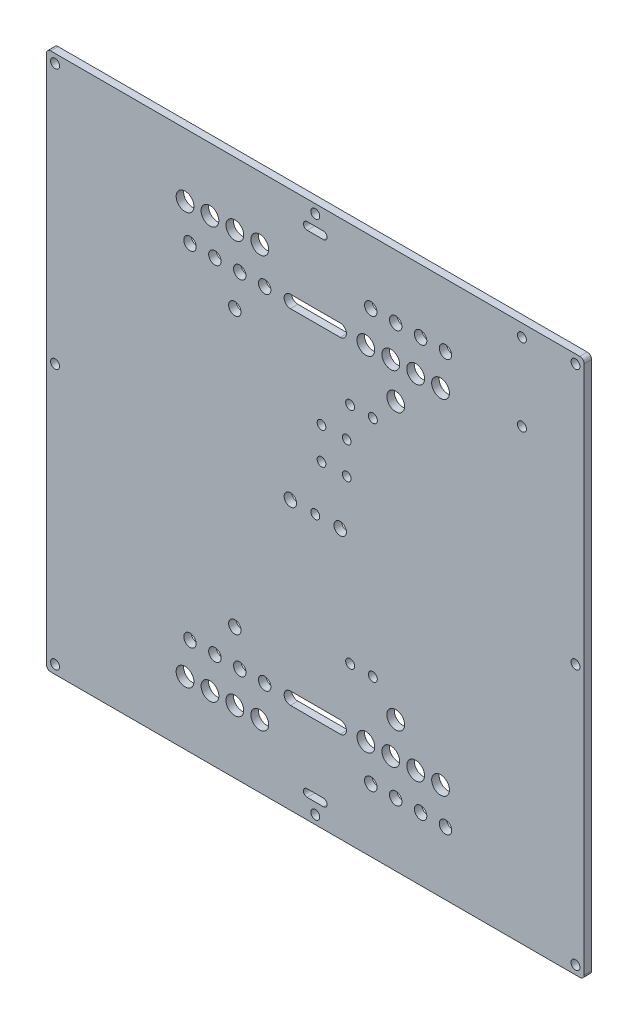
SolidWorks part; units mm, degrees
ref_plane "Plan de face" through (0, 0, 0) normal (0, 0, 1) x (1, 0, 0)
ref_plane "Plan de dessus" through (0, 0, 0) normal (0, 1, 0) x (1, 0, 0)
ref_plane "Plan de droite" through (0, 0, 0) normal (1, 0, 0) x (0, 0, -1)
sketch "Esquisse1" plane through (0, 0, 0) normal (0, 0, 1) x (1, 0, 0)
  line L0 (-3.25, -98.62) -> (3.25, -98.62) construction
  line L1 (-106.25, -108) -> (106.25, -108)
  line L2 (-108, -106.25) -> (-108, 106.25)
  line L3 (-106.25, 108) -> (106.25, 108)
  line L4 (108, -106.25) -> (108, 106.25)
  line L5 (-108, -108) -> (108, 108) construction
  line L6 (-108, 108) -> (108, -108) construction
  line L7 (-3.25, -97.12) -> (3.25, -97.12)
  line L8 (-3.25, -100.12) -> (3.25, -100.12)
  line L9 (0, -98.62) -> (0, -104.5) construction
  line L10 (-10, -69) -> (10, -69) construction
  line L11 (-10, -66.5) -> (10, -66.5)
  line L12 (-10, -71.5) -> (10, -71.5)
  line L13 (0, -69) -> (0, -98.62) construction
  line L14 (-32.3, -55.35) -> (32.3, -55.35) construction
  line L15 (32.3, -55.35) -> (0, -55.35) construction
  line L16 (0, -55.35) -> (0, -69) construction
  line L17 (-108, 0) -> (108, 0) construction
  line L18 (14, -45) -> (23.12, -45) construction
  line L19 (-10, 0) -> (10, 0) construction
  line L20 (-3.25, 98.62) -> (3.25, 98.62) construction
  line L21 (-3.25, 97.12) -> (3.25, 97.12)
  line L22 (-3.25, 100.12) -> (3.25, 100.12)
  line L23 (-10, 69) -> (10, 69) construction
  line L24 (-10, 66.5) -> (10, 66.5)
  line L25 (-10, 71.5) -> (10, 71.5)
  line L26 (14, 45) -> (23.12, 45) construction
  line L27 (0, 55.35) -> (0, 69) construction
  line L28 (32.3, 55.35) -> (0, 55.35) construction
  line L29 (-32.3, 55.35) -> (32.3, 55.35) construction
  line L30 (0, 69) -> (0, 98.62) construction
  line L31 (83, 103) -> (83, 72) construction
  arc A0 (-106.25, -108) -> (-108, -106.25) centre (-106.25, -106.25) cw
  arc A1 (106.25, -108) -> (108, -106.25) centre (106.25, -106.25) ccw
  arc A2 (106.25, 108) -> (108, 106.25) centre (106.25, 106.25) cw
  arc A3 (-108, 106.25) -> (-106.25, 108) centre (-106.25, 106.25) cw
  circle A4 centre (-104.5, 104.5) radius 1.8
  circle A5 centre (0, 104.5) radius 1.8
  circle A6 centre (104.5, 104.5) radius 1.8
  circle A7 centre (-104.5, 0) radius 1.8
  circle A8 centre (0, 0) radius 1.8
  circle A9 centre (104.5, 0) radius 1.8
  circle A10 centre (-104.5, -104.5) radius 1.8
  circle A11 centre (0, -104.5) radius 1.8
  circle A12 centre (104.5, -104.5) radius 1.8
  circle A13 centre (-52.3, -82.65) radius 3.57
  circle A14 centre (-42.3, -82.65) radius 3.57
  circle A15 centre (-32.3, -82.65) radius 3.57
  circle A16 centre (-22.3, -82.65) radius 3.57
  arc A17 (-3.25, -97.12) -> (-3.25, -100.12) centre (-3.25, -98.62) ccw
  arc A18 (3.25, -100.12) -> (3.25, -97.12) centre (3.25, -98.62) ccw
  circle A19 centre (-50.32, -69) radius 2.5
  circle A20 centre (-40.32, -69) radius 2.5
  circle A21 centre (-30.32, -69) radius 2.5
  circle A22 centre (-20.32, -69) radius 2.5
  arc A23 (-10, -66.5) -> (-10, -71.5) centre (-10, -69) ccw
  arc A24 (10, -71.5) -> (10, -66.5) centre (10, -69) ccw
  circle A25 centre (42.3, -82.65) radius 2.5
  circle A26 centre (32.3, -82.65) radius 2.5
  circle A27 centre (22.3, -82.65) radius 2.5
  circle A28 centre (52.3, -82.65) radius 2.5
  circle A29 centre (50.32, -69) radius 3.57
  circle A30 centre (40.32, -69) radius 3.57
  circle A31 centre (30.32, -69) radius 3.57
  circle A32 centre (20.32, -69) radius 3.57
  circle A33 centre (-32.3, -55.35) radius 2.5
  circle A34 centre (32.3, -55.35) radius 3.57
  circle A35 centre (14, -45) radius 1.8
  circle A36 centre (23.12, -45) radius 1.8
  circle A37 centre (-10, 0) radius 2.5
  circle A38 centre (10, 0) radius 2.5
  circle A39 centre (2.5, 32.3) radius 1.75
  circle A40 centre (12.64, 32.3) radius 1.75
  circle A41 centre (2.5, 19.47) radius 1.75
  circle A42 centre (12.64, 19.47) radius 1.75
  arc A43 (-3.25, 97.12) -> (-3.25, 100.12) centre (-3.25, 98.62) cw
  arc A44 (3.25, 100.12) -> (3.25, 97.12) centre (3.25, 98.62) cw
  arc A45 (-10, 66.5) -> (-10, 71.5) centre (-10, 69) cw
  arc A46 (10, 71.5) -> (10, 66.5) centre (10, 69) cw
  circle A47 centre (23.12, 45) radius 1.8
  circle A48 centre (14, 45) radius 1.8
  circle A49 centre (32.3, 55.35) radius 3.57
  circle A50 centre (-32.3, 55.35) radius 2.5
  circle A51 centre (20.32, 69) radius 3.57
  circle A52 centre (30.32, 69) radius 3.57
  circle A53 centre (40.32, 69) radius 3.57
  circle A54 centre (50.32, 69) radius 3.57
  circle A55 centre (52.3, 82.65) radius 2.5
  circle A56 centre (22.3, 82.65) radius 2.5
  circle A57 centre (32.3, 82.65) radius 2.5
  circle A58 centre (42.3, 82.65) radius 2.5
  circle A59 centre (-20.32, 69) radius 2.5
  circle A60 centre (-30.32, 69) radius 2.5
  circle A61 centre (-40.32, 69) radius 2.5
  circle A62 centre (-50.32, 69) radius 2.5
  circle A63 centre (-22.3, 82.65) radius 3.57
  circle A64 centre (-32.3, 82.65) radius 3.57
  circle A65 centre (-42.3, 82.65) radius 3.57
  circle A66 centre (-52.3, 82.65) radius 3.57
  circle A67 centre (83, 103) radius 1.8
  circle A68 centre (83, 72) radius 1.8
  point P0 (0, 0)
  point P46 (0, -98.62)
  point P62 (0, -69)
  point P109 (0, 98.62)
  point P116 (0, 69)
  dimension "D2" = 1.75
  dimension "D3" = 3.6
  dimension "D7" = 7.14
  dimension "D15" = 5
  dimension "D26" = 57.68
  dimension "D27" = 4
  dimension "D28" = 10
  dimension "D29" = 5
  dimension "D24" = 7.14
  dimension "D30" = 5
  dimension "D31" = 7.14
  dimension "D34" = 3.6
  dimension "D35" = 3.6
  dimension "D39" = 5
  dimension "D40" = 5
  dimension "D43" = 3.5
  dimension "D51" = 3.6
  dimension "D52" = 3.6
  dimension "D1" = 216
  dimension "D4" = 104.5
  dimension "D8" = 160.3
  dimension "D9" = 25.35
  dimension "D11" = 10
  dimension "D12" = 6.5
  dimension "D13" = 3
  dimension "D14" = 9.38
  dimension "D16" = 158.32
  dimension "D17" = 39
  dimension "D19" = 10
  dimension "D20" = 5
  dimension "D21" = 20
  dimension "D22" = 4
  dimension "D23" = 10
  dimension "D25" = 55.7
  dimension "D32" = 64.6
  dimension "D33" = 110.7
  dimension "D36" = 9.12
  dimension "D37" = 63
  dimension "D38" = 122
  dimension "D41" = 10
  dimension "D42" = 10
  dimension "D46" = 10.14
  dimension "D47" = 12.83
  dimension "D48" = 75.7
  dimension "D49" = 110.5
  dimension "D50" = 21.5
  dimension "D53" = 36
  dimension "D54" = 31
  dimension "D5" = 3
  dimension "D6" = 3
  dimension "D10" = 4
  dimension "D18" = 4
  dimension "D44" = 2
  dimension "D45" = 2
extrude "Boss.-Extru.1" add sketch "Esquisse1" along normal mid plane 3
